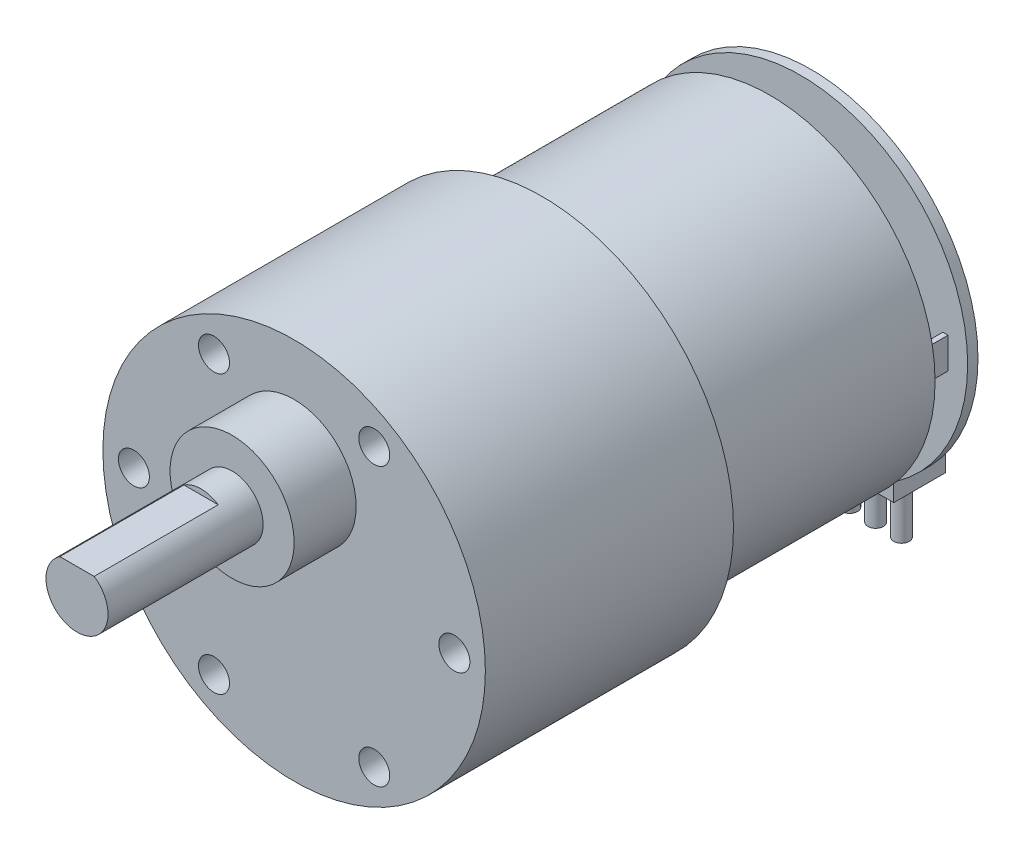
SolidWorks part; units mm, degrees
ref_plane "정면" through (0, 0, 0) normal (0, 0, 1) x (1, 0, 0)
ref_plane "윗면" through (0, 0, 0) normal (0, 1, 0) x (1, 0, 0)
ref_plane "우측면" through (0, 0, 0) normal (1, 0, 0) x (0, 0, -1)
sketch "스케치2" plane through (0, 0, 0) normal (0, 0, 1) x (1, 0, 0)
  circle A0 centre (0, 0) radius 18.5
  dimension "D1" = 37
extrude "보스-돌출1" add sketch "스케치2" against normal blind 24
sketch "스케치3" plane through (0, 0, -24) normal (0, 0, -1) x (-1, 0, 0)
  circle A0 centre (0, 0) radius 16
  dimension "D1" = 32
extrude "보스-돌출2" add sketch "스케치3" along normal blind 22
sketch "스케치4" plane through (0, 0, -46) normal (0, 0, -1) x (-1, 0, 0)
  line L0 (-22.2962, 0) -> (22.2962, 0) construction
  line L1 (13.75, 1.5) -> (14.25, 1.5)
  line L2 (13.75, 1.5) -> (13.75, -1.5)
  line L3 (13.75, -1.5) -> (14.25, -1.5)
  line L4 (14.25, 1.5) -> (14.25, -1.5)
  line L5 (13.75, 1.5) -> (14.25, -1.5) construction
  line L6 (13.75, -1.5) -> (14.25, 1.5) construction
  line L7 (-14.25, 1.5) -> (-13.75, 1.5)
  line L8 (-14.25, 1.5) -> (-14.25, -1.5)
  line L9 (-14.25, -1.5) -> (-13.75, -1.5)
  line L10 (-13.75, 1.5) -> (-13.75, -1.5)
  line L11 (-14.25, 1.5) -> (-13.75, -1.5) construction
  line L12 (-14.25, -1.5) -> (-13.75, 1.5) construction
  circle A0 centre (0, 0) radius 3
  point P3 (14, 0)
  point P8 (-14, 0)
  point P13 (0, 0)
  point P17 (0, 0)
  point P18 (0, 0)
  point P19 (0, 0)
  dimension "D4" = 14
  dimension "D5" = 6
  dimension "D1" = 0.5
  dimension "D2" = 3
  dimension "D3" = 14
extrude "보스-돌출3" add sketch "스케치4" along normal blind 3
sketch "스케치5" plane through (0, 0, -49) normal (0, 0, -1) x (-1, 0, 0)
  circle A0 centre (0, 0) radius 16.15
  dimension "D1" = 32.3
extrude "보스-돌출4" add sketch "스케치5" along normal blind 1
sketch "스케치6" plane through (0, 0, -50) normal (0, 0, -1) x (-1, 0, 0)
  line L0 (0, 16.15) -> (0, -16.15) construction
  line L1 (-8, -6.85) -> (8, -6.85)
  line L2 (-8, -6.85) -> (-8, -16.15)
  line L3 (-8, -16.15) -> (8, -16.15)
  line L4 (8, -6.85) -> (8, -16.15)
  line L5 (-8, -6.85) -> (8, -16.15) construction
  line L6 (-8, -16.15) -> (8, -6.85) construction
  circle A0 centre (0, 0) radius 16.15 construction
  circle A2 centre (0, 0) radius 6.8
  point P0 (0, -11.5)
  point P10 (0, 0)
  point P14 (-11.5, -12.6276)
  point P16 (0, -12.6144)
  dimension "D3" = 13.6
  dimension "D1" = 16
  dimension "D2" = 9.3
extrude "보스-돌출7" add sketch "스케치6" along normal blind 5
sketch "스케치7" plane through (0, -16.15, 0) normal (0, -1, 0) x (1, 0, 0)
  line L0 (-8, -52.5) -> (8, -52.5) construction
  line L1 (-8, -55) -> (-8, -50) construction
  line L2 (8, -55) -> (8, -50) construction
  circle A0 centre (-6.25, -52.5) radius 0.75
  circle A1 centre (-3.75, -52.5) radius 0.75
  circle A2 centre (-1.25, -52.5) radius 0.75
  circle A3 centre (1.25, -52.5) radius 0.75
  circle A4 centre (3.75, -52.5) radius 0.75
  circle A5 centre (6.25, -52.5) radius 0.75
  dimension "D1" = 1.5
  dimension "D2" = 1.75
  dimension "D3" = 6
extrude "보스-돌출8" add sketch "스케치7" along normal blind 5
sketch "스케치8" plane through (0, 0, 0) normal (0, 0, 1) x (1, 0, 0)
  circle A0 centre (0, 7.5) radius 6
  circle A1 centre (0, 0) radius 18.5 construction
  dimension "D1" = 7.5
  dimension "D2" = 12
extrude "보스-돌출9" add sketch "스케치8" along normal blind 6
sketch "스케치9" plane through (0, 0, 6) normal (0, 0, 1) x (1, 0, 0)
  circle A0 centre (0, 7.5) radius 3
  dimension "D1" = 6
extrude "보스-돌출10" add sketch "스케치9" along normal blind 15
sketch "스케치10" plane through (0, 0, 21) normal (0, 0, 1) x (1, 0, 0)
  line L3 (-1.6583, 10) -> (1.6583, 10)
  arc A0 (1.6583, 10) -> (-1.6583, 10) centre (0, 7.5) ccw
extrude "컷-돌출1" cut sketch "스케치10" against normal blind 12
sketch "스케치11" plane through (0, 0, 0) normal (0, 0, 1) x (1, 0, 0)
  circle A0 centre (0, 0) radius 15.5 construction
  circle A1 centre (15.5, 0) radius 1.5
  circle A2 centre (7.75, -13.4234) radius 1.5
  circle A3 centre (-7.75, -13.4234) radius 1.5
  circle A4 centre (-15.5, 0) radius 1.5
  circle A5 centre (-7.75, 13.4234) radius 1.5
  circle A6 centre (7.75, 13.4234) radius 1.5
  point P18 (0, 0)
  dimension "D1" = 31
  dimension "D2" = 3
  dimension "D3" = 6
extrude "컷-돌출2" cut sketch "스케치11" against normal blind 3.5
